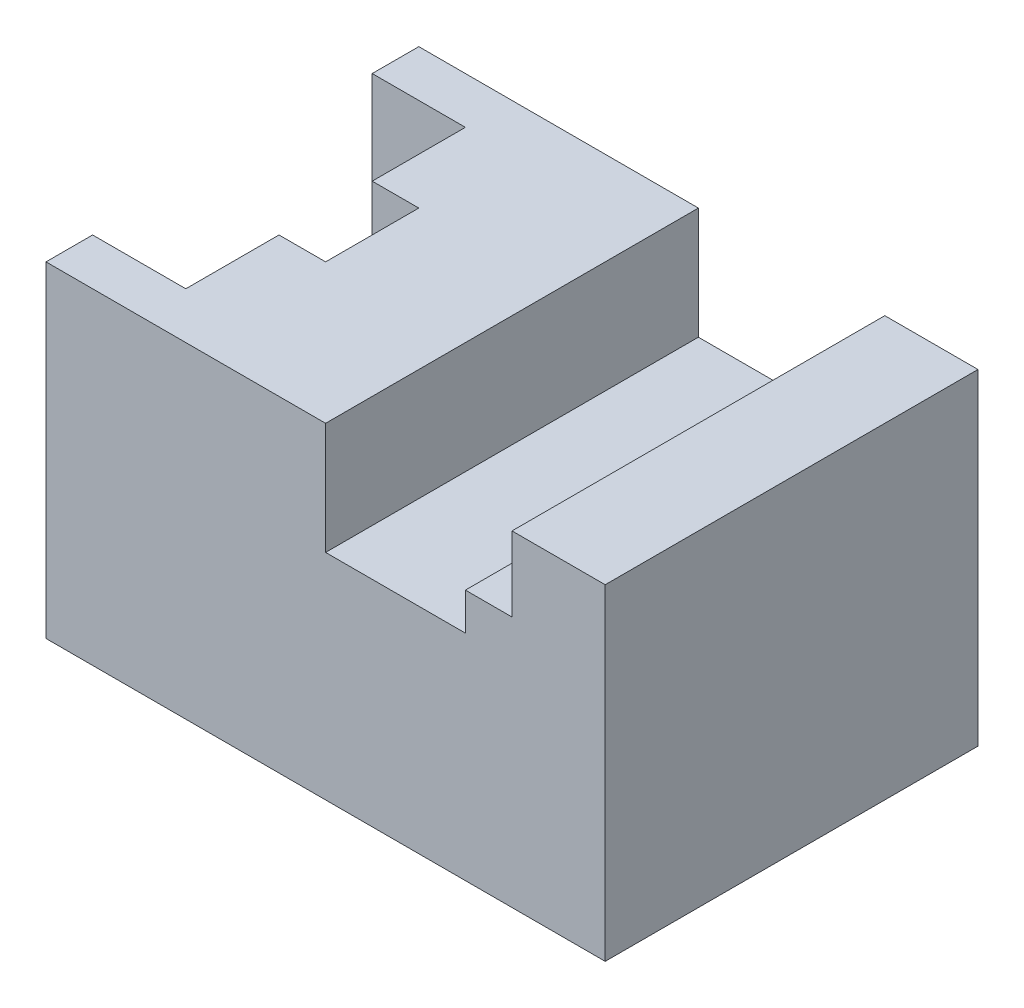
SolidWorks part; units mm, degrees
material "Сталь"
ref_plane "Спереди" through (0, 0, 0) normal (0, 0, 1) x (1, 0, 0)
ref_plane "Сверху" through (0, 0, 0) normal (0, 1, 0) x (1, 0, 0)
ref_plane "Справа" through (0, 0, 0) normal (1, 0, 0) x (0, 0, -1)
sketch "Эскиз1" plane through (0, 0, 0) normal (0, 0, 1) x (1, 0, 0)
  line L1 (-30, -17.5) -> (30, -17.5)
  line L2 (-30, -17.5) -> (-30, 17.5)
  line L3 (-30, 17.5) -> (30, 17.5)
  line L4 (30, -17.5) -> (30, 17.5)
  line L5 (-30, -17.5) -> (30, 17.5) construction
  line L6 (-30, 17.5) -> (30, -17.5) construction
  point P0 (0, 0)
  dimension "D1" = 35
  dimension "D2" = 60
extrude "Бобышка-Вытянуть1" add sketch "Эскиз1" along normal mid plane 40
sketch "Эскиз2" plane through (0, 17.5, 0) normal (0, 1, 0) x (1, 0, 0)
  line L0 (-30, 0) -> (30, 0) construction
  line L1 (-30, -20) -> (-30, 20) construction
  line L2 (30, -20) -> (30, 20) construction
  line L4 (-30, -15) -> (-20, -15)
  line L5 (-30, -15) -> (-30, 15)
  line L6 (-30, 15) -> (-20, 15)
  line L7 (-20, -15) -> (-20, 15)
  line L8 (-30, -15) -> (-20, 15) construction
  line L9 (-30, 15) -> (-20, -15) construction
  line L10 (-15, -5) -> (-20, -5)
  line L11 (-15, -5) -> (-15, 5)
  line L12 (-15, 5) -> (-20, 5)
  line L13 (-20, -5) -> (-20, 5)
  line L14 (-15, -5) -> (-20, 5) construction
  line L15 (-15, 5) -> (-20, -5) construction
  point P6 (-25, 0)
  point P11 (-17.5, 0)
  line M2 (-30, 20) -> (-30, -20)
  dimension "D1" = 30
  dimension "D2" = 10
  dimension "D3" = 10
  dimension "D4" = 5
extrude "Вырез-Вытянуть1" cut sketch "Эскиз2" against normal offset from surface (25 mm away) 10 contours L4 L7 L6 M2 | L11 L12 L7 L10 up to face at (0, -17.5, 0)
sketch "Эскиз3" plane through (0, 0, 20) normal (0, 0, 1) x (1, 0, 0)
  line L0 (30, 17.5) -> (-30, 17.5) construction
  line L1 (0, 5.5) -> (15, 5.5)
  line L2 (0, 5.5) -> (0, 17.5)
  line L3 (0, 17.5) -> (15, 17.5)
  line L4 (15, 5.5) -> (15, 17.5)
  line L5 (0, 5.5) -> (15, 17.5) construction
  line L6 (0, 17.5) -> (15, 5.5) construction
  line L7 (30, -17.5) -> (30, 17.5) construction
  line L8 (15, 9.5) -> (20, 9.5)
  line L9 (15, 9.5) -> (15, 17.5)
  line L10 (15, 17.5) -> (20, 17.5)
  line L11 (20, 9.5) -> (20, 17.5)
  line L12 (15, 9.5) -> (20, 17.5) construction
  line L13 (15, 17.5) -> (20, 9.5) construction
  point P0 (7.5, 11.5)
  point P7 (17.5, 13.5)
  line M2 (30, 17.5) -> (-30, 17.5)
  dimension "D1" = 12
  dimension "D2" = 8
  dimension "D3" = 10
  dimension "D4" = 5
  dimension "D5" = 15
extrude "Вырез-Вытянуть2" cut sketch "Эскиз3" against normal through all contours L1 L4 L2 M2 | L8 L11 L4 M2
